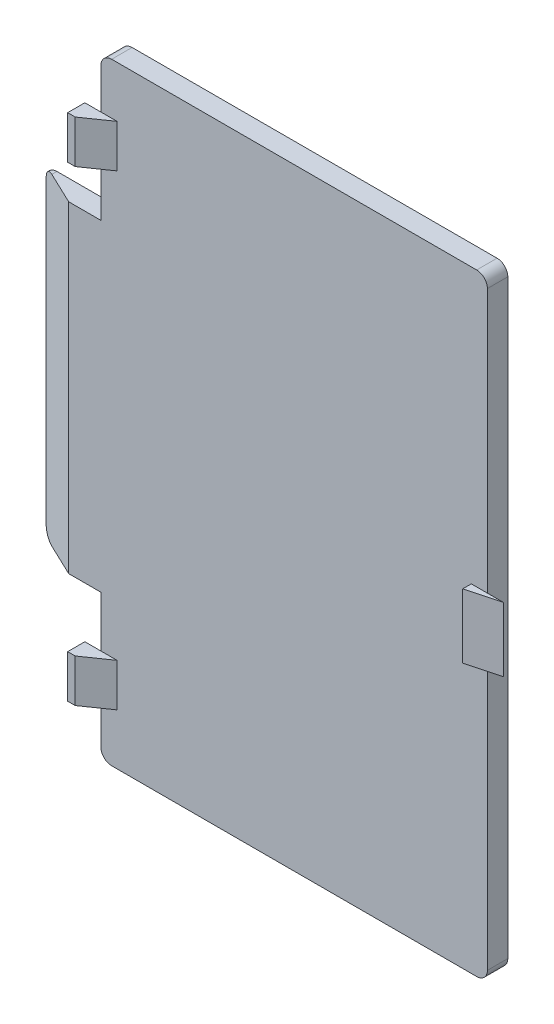
SolidWorks part; units mm, degrees
ref_plane "Plano frontal" through (0, 0, 0) normal (0, 0, 1) x (1, 0, 0)
ref_plane "Plano superior" through (0, 0, 0) normal (0, 1, 0) x (1, 0, 0)
ref_plane "Plano direito" through (0, 0, 0) normal (1, 0, 0) x (0, 0, -1)
sketch "Esboço1" plane through (0, 0, 0) normal (0, 0, 1) x (1, 0, 0)
  line L0 (-23.8013, -0.3182) -> (-23.8013, -28.3182)
  line L1 (-15.8013, 14.1818) -> (18.1987, 14.1818)
  line L2 (-16.8013, 13.1818) -> (-16.8013, 0.6818)
  line L3 (-15.8013, -42.8182) -> (18.1987, -42.8182)
  line L4 (19.1987, 13.1818) -> (19.1987, -41.8182)
  line L6 (-22.8013, 0.6818) -> (-16.8013, 0.6818)
  line L7 (-22.8013, -29.3182) -> (-16.8013, -29.3182)
  line L8 (-16.8013, -29.3182) -> (-16.8013, -41.8182)
  arc A0 (-23.8013, -0.3182) -> (-22.8013, 0.6818) centre (-22.8013, -0.3182) cw
  arc A1 (-23.8013, -28.3182) -> (-22.8013, -29.3182) centre (-22.8013, -28.3182) ccw
  arc A2 (-16.8013, -41.8182) -> (-15.8013, -42.8182) centre (-15.8013, -41.8182) ccw
  arc A3 (18.1987, -42.8182) -> (19.1987, -41.8182) centre (18.1987, -41.8182) ccw
  arc A4 (18.1987, 14.1818) -> (19.1987, 13.1818) centre (18.1987, 13.1818) cw
  arc A5 (-15.8013, 14.1818) -> (-16.8013, 13.1818) centre (-15.8013, 13.1818) ccw
  point P14 (-16.8013, -42.8182)
  point P19 (19.1987, 14.1818)
  point P22 (-16.8013, 14.1818)
  dimension "D3" = 1
  dimension "D4" = 1
  dimension "D5" = 1
  dimension "D1" = 57
  dimension "D2" = 36
extrude "Ressalto-extrusão2" add sketch "Esboço1" along normal blind 1.9
sketch "Esboço3" plane through (-16.8013, 0, 0) normal (-1, 0, 0) x (0, 0, 1)
  line L0 (1.9, -35.5682) -> (1.9, -34.0582)
  line L1 (1.9, -29.3182) -> (1.9, -41.8182) construction
  line L2 (1.9, -34.0582) -> (3.5, -34.0582)
  line L3 (3.5, -34.0582) -> (3.5, -38.0582)
  line L4 (3.5, -38.0582) -> (1.9, -38.0582)
  line L5 (1.9, -38.0582) -> (1.9, -35.5682)
  line L6 (1.9, -29.3182) -> (0, -29.3182) construction
  line L7 (1.9, 6.9318) -> (1.9, 9.4218)
  line L8 (1.9, 13.1818) -> (1.9, 0.6818) construction
  line L9 (1.9, 9.4218) -> (3.5, 9.4218)
  line L10 (3.5, 9.4218) -> (3.5, 5.4218)
  line L11 (3.5, 5.4218) -> (1.9, 5.4218)
  line L12 (1.9, 5.4218) -> (1.9, 6.9318)
  line L13 (1.9, 0.6818) -> (0, 0.6818) construction
  dimension "D1" = 4.74
  dimension "D2" = 4.74
extrude "Ressalto-extrusão3" add sketch "Esboço3" along normal mid plane 3
sketch "Esboço4" plane through (0, 0.6818, 0) normal (0, 1, 0) x (1, 0, 0)
  line L0 (-23.8013, 0) -> (-19.8013, -1.9)
  line L1 (-16.8013, -1.9) -> (-22.8013, -1.9) construction
  line L2 (-19.8013, -1.9) -> (-23.8013, -1.9)
  line L3 (-23.8013, -1.9) -> (-23.8013, 0)
  dimension "D1" = 4
extrude "Corte-extrusão1" cut sketch "Esboço4" against normal blind 100
sketch "Esboço5" plane through (19.1987, 0, 0) normal (1, 0, 0) x (0, 0, -1)
  line L0 (-1.9, -11.3905) -> (-1.9, -17.3905)
  line L1 (-1.9, -41.8182) -> (-1.9, 13.1818) construction
  line L2 (-1.9, -17.3905) -> (-2.7, -17.3905)
  line L3 (-1.9, -11.3905) -> (-2.7, -11.3905)
  line L4 (-2.7, -11.3905) -> (-2.7, -17.3905)
extrude "Ressalto-extrusão4" add sketch "Esboço5" along normal mid plane 3
sketch "Esboço6" plane through (0, -17.3905, 0) normal (0, -1, 0) x (-1, 0, 0)
  line L0 (-20.6987, -1.9) -> (-17.6987, -2.7)
  line L1 (-17.6987, -2.7) -> (-20.6987, -2.7)
  line L2 (-20.6987, -2.7) -> (-20.6987, -1.9)
extrude "Corte-extrusão2" cut sketch "Esboço6" against normal blind 100 contours L2 L0 L1
sketch "Esboço7" plane through (0, 9.4218, 0) normal (0, 1, 0) x (1, 0, 0)
  line L0 (-15.3013, -1.9) -> (-17.6013, -3.5)
  line L1 (-18.3013, -3.5) -> (-15.3013, -3.5) construction
  line L2 (-15.3013, -1.9) -> (-15.3013, -3.5)
  line L3 (-15.3013, -3.5) -> (-17.6013, -3.5)
extrude "Corte-extrusão3" cut sketch "Esboço7" against normal blind 1000
